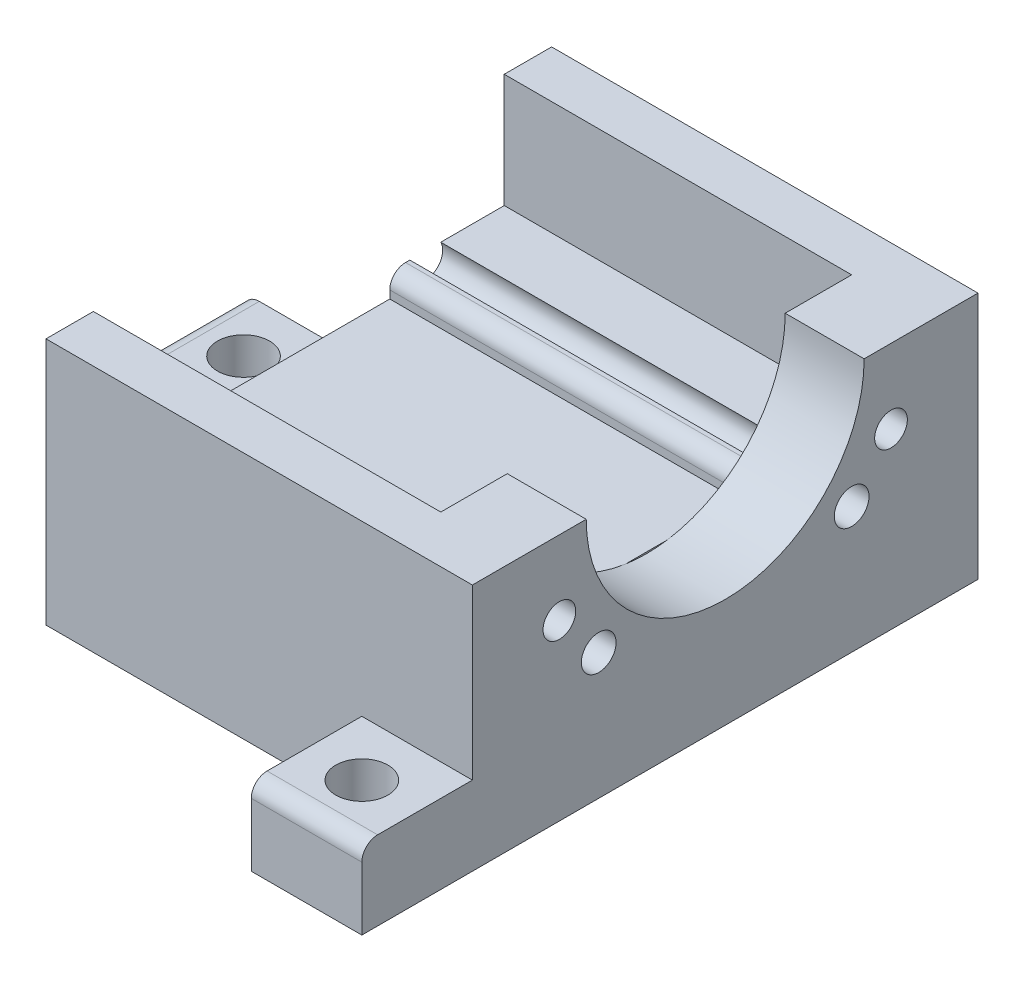
SolidWorks part; units mm, degrees
ref_plane "Front" through (0, 0, 0) normal (0, 0, 1) x (1, 0, 0)
ref_plane "Top" through (0, 0, 0) normal (0, 1, 0) x (1, 0, 0)
ref_plane "Right" through (0, 0, 0) normal (1, 0, 0) x (0, 0, -1)
sketch "Sketch1" plane through (0, 0, 0) normal (1, 0, 0) x (0, 0, -1)
  line L0 (-13.0089, 0) -> (13.0089, 0)
  line L1 (13.0089, 0) -> (13.0089, 8.5)
  line L2 (13.0089, 8.5) -> (5.7589, 8.5)
  line L3 (5.7589, 8.5) -> (5.7589, 7)
  line L4 (5.7589, 7) -> (-5.7589, 7)
  line L5 (-5.7589, 7) -> (-5.7589, 8.5)
  line L6 (-5.7589, 8.5) -> (-13.0089, 8.5)
  line L7 (-13.0089, 8.5) -> (-13.0089, 0)
  dimension "D1" = 8.5
  dimension "D2" = 7.25
  dimension "D3" = 26.0178
  dimension "D4" = 1.5
extrude "Boss-Extrude1" add sketch "Sketch1" along normal mid plane 22
sketch "Sketch3" plane through (0, 0, 0) normal (0, -1, 0) x (1, 0, 0)
  line L1 (-11, -13.0089) -> (11, -13.0089)
  line L2 (-11, -13.0089) -> (-11, -16.0089)
  line L3 (-11, -16.0089) -> (11, -16.0089)
  line L4 (11, -13.0089) -> (11, -16.0089)
  line L5 (-11, 13.0089) -> (11, 13.0089)
  line L6 (-11, 13.0089) -> (-11, 16.0089)
  line L7 (-11, 16.0089) -> (11, 16.0089)
  line L8 (11, 13.0089) -> (11, 16.0089)
  dimension "D1" = 3
  dimension "D2" = 22
  dimension "D3" = 3
  dimension "D4" = 22
extrude "Boss-Extrude2" add sketch "Sketch3" against normal blind 15.7
sketch "Sketch4" plane through (11, 0, 0) normal (1, 0, 0) x (0, 0, -1)
  line L0 (0, 0) -> (0, 15.7) construction
  line L1 (-16.0089, 0) -> (16.0089, 0) construction
  line L2 (-8.8, 15.7) -> (-16.0089, 15.7)
  line L3 (-16.0089, 15.7) -> (-16.0089, 0) construction
  line L4 (-16.0089, 15.7) -> (-16.0089, 0)
  line L5 (-16.0089, 0) -> (16.0089, 0)
  line L6 (16.0089, 0) -> (16.0089, 15.7)
  line L7 (16.0089, 15.7) -> (16.0089, 0) construction
  line L8 (16.0089, 15.7) -> (8.8, 15.7)
  arc A0 (-8.8, 15.7) -> (8.8, 15.7) centre (0, 15.7) ccw
  dimension "D1" = 8.8
  dimension "D2" = 15.7
extrude "Boss-Extrude3" add sketch "Sketch4" along normal blind 5
sketch "Sketch5" plane through (16, 0, 0) normal (1, 0, 0) x (0, 0, -1)
  line L0 (-16.0089, 11) -> (-10.5, 11) construction
  line L1 (-16.0089, 15.7) -> (-16.0089, 0) construction
  line L2 (-10.5, 11) -> (-10.5, 0) construction
  line L3 (-16.0089, 0) -> (16.0089, 0) construction
  line L4 (0, 0) -> (0, 15.7) construction
  line L5 (-16.0089, 8) -> (-8.0089, 8) construction
  line L6 (-8.0089, 8) -> (-8.0089, 0) construction
  circle A0 centre (-10.5, 11) radius 1.035
  circle A1 centre (10.5, 11) radius 1.035
  circle A2 centre (-8.0089, 8) radius 1.1
  circle A3 centre (8.0089, 8) radius 1.1
  dimension "D3" = 2.07
  dimension "D4" = 2.2
  dimension "D1" = 5.5089
  dimension "D2" = 11
  dimension "D5" = 8
  dimension "D6" = 8
extrude "Cut-Extrude1" cut sketch "Sketch5" against normal through all
sketch "Sketch6" plane through (0, 0, 0) normal (0, -1, 0) x (1, 0, 0)
  line L5 (0, 0) -> (-11, 0) construction
  line L14 (-11, 16.0089) -> (-11, -16.0089) construction
  line L15 (16, 16.0089) -> (9, 16.0089)
  line L16 (-11, 3.5) -> (-18, 3.5)
  line L17 (-11, 3.5) -> (-11, -3.5)
  line L18 (-11, -3.5) -> (-18, -3.5)
  line L19 (-18, 3.5) -> (-18, -3.5)
  line L20 (16, 16.0089) -> (16, 23.0089)
  line L21 (16, 23.0089) -> (9, 23.0089)
  line L22 (9, 16.0089) -> (9, 23.0089)
  dimension "D1" = 7
  dimension "D2" = 7
  dimension "D3" = 7
  dimension "D4" = 7
extrude "Boss-Extrude4" add sketch "Sketch6" against normal blind 5
sketch "Sketch7" plane through (0, 5, 0) normal (0, 1, 0) x (1, 0, 0)
  line L0 (-11, 0) -> (-18, 0) construction
  line L1 (-11, 3.5) -> (-11, -3.5) construction
  line L2 (-18, -3.5) -> (-18, 3.5) construction
  line L3 (-14.5, 3.5) -> (-14.5, -3.5) construction
  line L4 (-18, 3.5) -> (-11, 3.5) construction
  line L5 (-11, -3.5) -> (-18, -3.5) construction
  line L6 (12.5, -16.0089) -> (12.5, -23.0089) construction
  line L9 (9, -19.5089) -> (16, -19.5089) construction
  line L12 (9, -23.0089) -> (9, -16.0089) construction
  line L13 (9, -16.0089) -> (16, -16.0089) construction
  line L14 (16, -23.0089) -> (9, -23.0089) construction
  line L15 (16, -16.0089) -> (16, -23.0089) construction
  circle A0 centre (-14.5, 0) radius 1.65
  circle A1 centre (12.5, -19.5089) radius 1.65
  dimension "D1" = 3.3
extrude "Cut-Extrude2" cut sketch "Sketch7" against normal through all
fillet "Fillet1" radius 1 4 edges at (-18, 5, 0) (12.5, 5, 23.0089) (0, 8.5, 5.7589) (0, 8.5, -5.7589)
